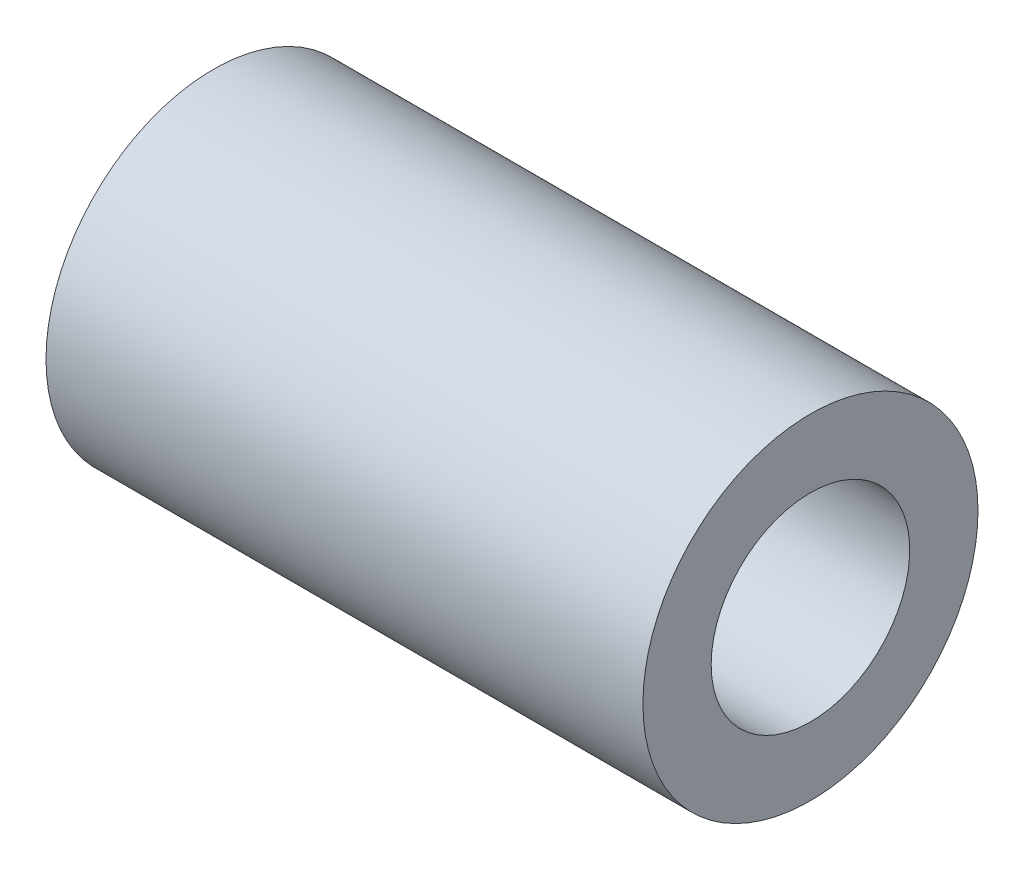
SolidWorks part; units mm, degrees
ref_plane "前视基准面" through (0, 0, 0) normal (0, 0, 1) x (1, 0, 0)
ref_plane "上视基准面" through (0, 0, 0) normal (0, 1, 0) x (1, 0, 0)
ref_plane "右视基准面" through (0, 0, 0) normal (1, 0, 0) x (0, 0, -1)
sketch "草图1" plane through (0, 0, 0) normal (1, 0, 0) x (0, 0, -1)
  circle A0 centre (0, 0) radius 16
  circle A1 centre (0, 0) radius 27
extrude "凸台-拉伸1" add sketch "草图1" along normal blind 96.2
